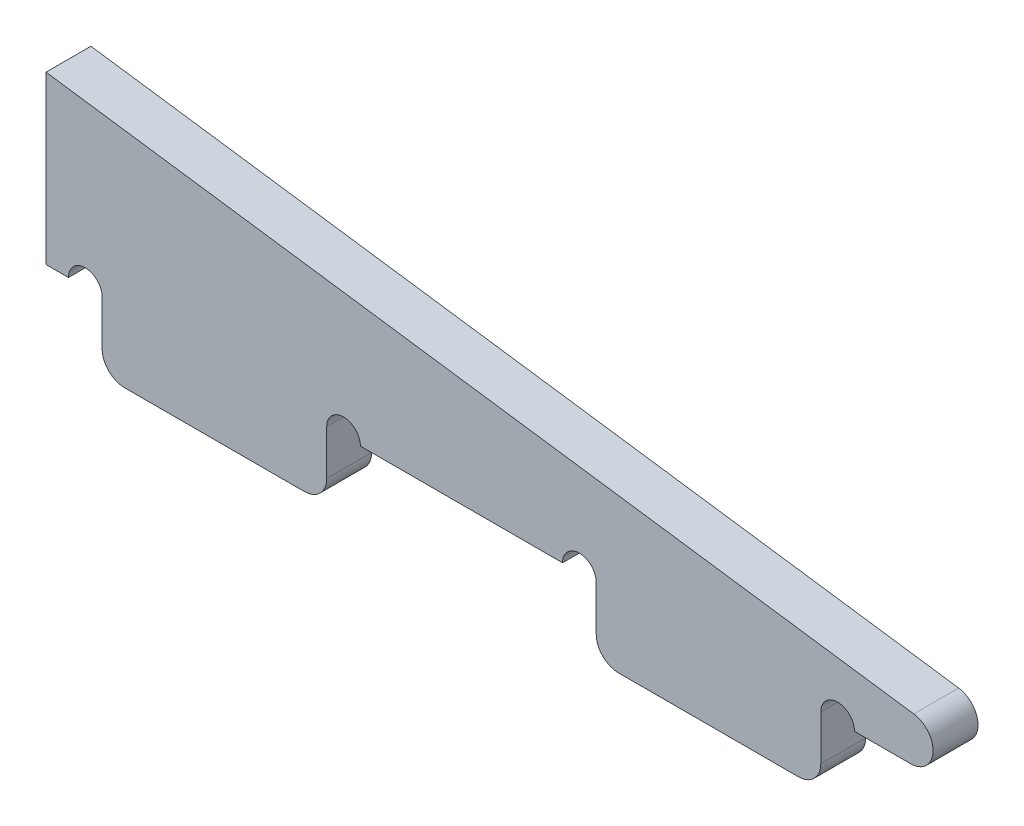
SolidWorks part; units mm, degrees
material "Thornel Mat VMA"
ref_plane "前视基准面" through (0, 0, 0) normal (0, 0, 1) x (1, 0, 0)
ref_plane "上视基准面" through (0, 0, 0) normal (0, 1, 0) x (1, 0, 0)
ref_plane "右视基准面" through (0, 0, 0) normal (1, 0, 0) x (0, 0, -1)
sketch "草图1" plane through (0, 0, 0) normal (0, 0, 1) x (1, 0, 0)
  line L0 (4.1392, 1.9903) -> (-34.5, 7.4206)
  line L1 (-34.5, 7.4206) -> (-34.5, 0)
  line L2 (-34.5, 0) -> (-32, 0)
  line L3 (-32, 0) -> (-32, -3)
  line L4 (-32, -3) -> (-22, -3)
  line L5 (-22, -3) -> (-22, 0)
  line L6 (-22, 0) -> (-10, 0)
  line L7 (-10, 0) -> (-10, -3)
  line L8 (-10, -3) -> (0, -3)
  line L9 (0, -3) -> (0, 0)
  line L10 (0, 0) -> (4, 0)
  arc A0 (4, 0) -> (4.1392, 1.9903) centre (4, 1) ccw
  dimension "D6" = 1
  dimension "D1" = 3
  dimension "D2" = 10
  dimension "D3" = 12
  dimension "D4" = 2.5
  dimension "D5" = 8
  dimension "D7" = 4
extrude "凸台-拉伸1" add sketch "草图1" along normal blind 2
sketch "草图2" plane through (0, 0, 2) normal (0, 0, 1) x (1, 0, 0)
  line L0 (-34.5, 0) -> (-32, 0) construction
  line L1 (-22, 0) -> (-10, 0) construction
  line L2 (0, 0) -> (4, 0) construction
  circle A0 centre (-32.75, 0) radius 0.75
  circle A1 centre (-21.25, 0) radius 0.75
  circle A2 centre (-10.75, 0) radius 0.75
  circle A3 centre (0.75, 0) radius 0.75
  dimension "D1" = 1.5
extrude "切除-拉伸1" cut sketch "草图2" against normal through all
fillet "圆角1" radius 1 4 edges at (0, -3, 1) (-10, -3, 1) (-22, -3, 1) (-32, -3, 1)
